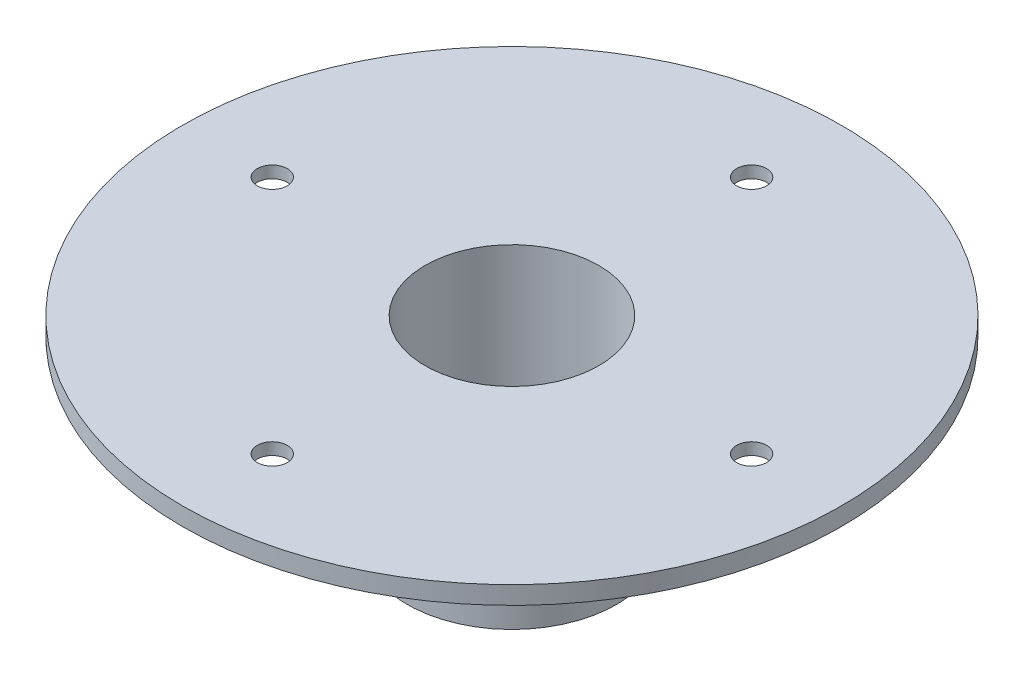
SolidWorks part; units mm, degrees
ref_plane "Front Plane" through (0, 0, 0) normal (0, 0, 1) x (1, 0, 0)
ref_plane "Top Plane" through (0, 0, 0) normal (0, 1, 0) x (1, 0, 0)
ref_plane "Right Plane" through (0, 0, 0) normal (1, 0, 0) x (0, 0, -1)
sketch "Sketch1" plane through (0, 0, 0) normal (0, 1, 0) x (1, 0, 0)
  circle A0 centre (0, 0) radius 55
  dimension "D1" = 110
extrude "Boss-Extrude1" add sketch "Sketch1" along normal blind 3
sketch "Sketch2" plane through (0, 0, 0) normal (0, -1, 0) x (1, 0, 0)
  circle A0 centre (0, 0) radius 17.5
  dimension "D1" = 35
extrude "Boss-Extrude2" add sketch "Sketch2" along normal blind 30
sketch "Sketch3" plane through (0, -30, 0) normal (0, -1, 0) x (1, 0, 0)
  circle A0 centre (0, 0) radius 14.5
  dimension "D1" = 29
extrude "Cut-Extrude1" cut sketch "Sketch3" against normal through all
sketch "Sketch4" plane through (0, 3, 0) normal (0, 1, 0) x (1, 0, 0)
  circle A1 centre (0, 40) radius 2.5
  circle A2 centre (40, 0) radius 2.5
  circle A3 centre (0, -40) radius 2.5
  circle A4 centre (-40, 0) radius 2.5
  point P12 (0, 0)
  dimension "D1" = 4
  dimension "D2" = 5
extrude "Cut-Extrude2" cut sketch "Sketch4" against normal through all
sketch "Sketch5" plane through (0, 0, 0) normal (0, -1, 0) x (1, 0, 0)
  circle A0 centre (0, 40) radius 9
  circle A1 centre (40, 0) radius 9
  circle A2 centre (0, -40) radius 9
  circle A3 centre (-40, 0) radius 9
  point P12 (0, 0)
  dimension "D1" = 18
  dimension "D2" = 4
extrude "Cut-Extrude3" cut sketch "Sketch5" against normal blind 1
